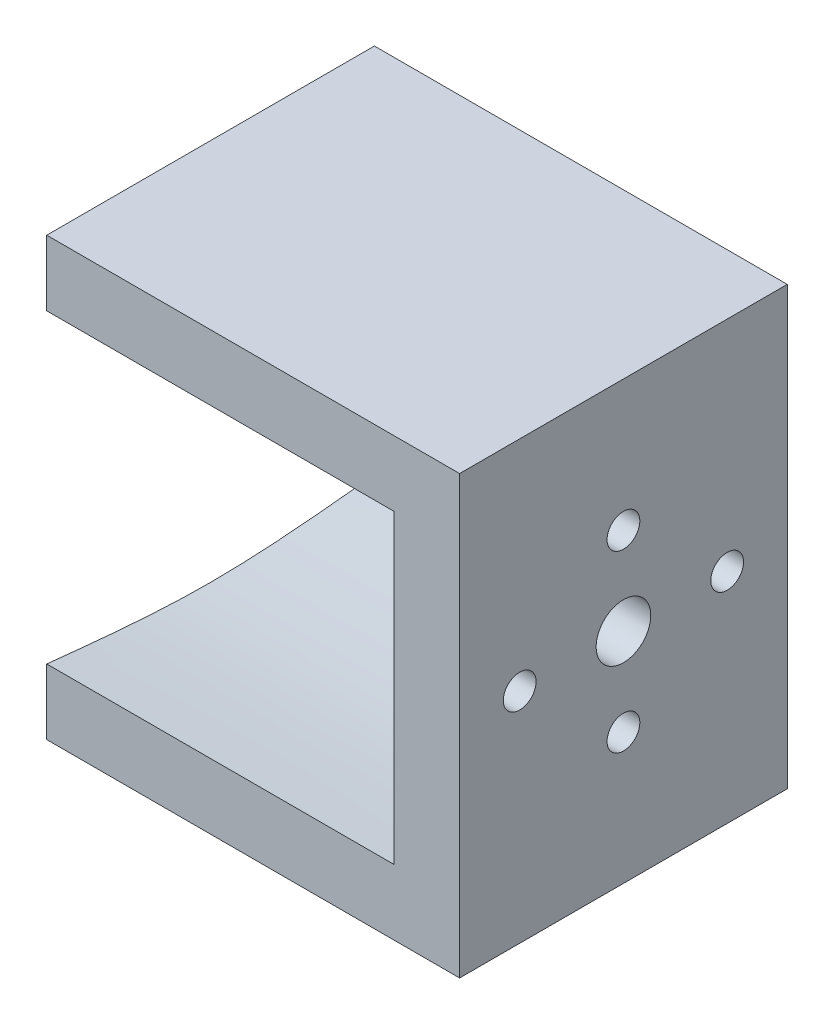
SolidWorks part; units mm, degrees
ref_plane "Front Plane" through (0, 0, 0) normal (0, 0, 1) x (1, 0, 0)
ref_plane "Top Plane" through (0, 0, 0) normal (0, 1, 0) x (1, 0, 0)
ref_plane "Right Plane" through (0, 0, 0) normal (1, 0, 0) x (0, 0, -1)
sketch "Sketch2" plane through (0, 0, 0) normal (0, 0, 1) x (1, 0, 0)
  line L0 (-18.9011, 20) -> (-18.9011, 14)
  line L1 (-18.9011, -20) -> (18.9011, -20)
  line L3 (-18.9011, 20) -> (18.9011, 20)
  line L4 (18.9011, -20) -> (18.9011, 20)
  line L5 (-18.9011, -20) -> (18.9011, 20) construction
  line L6 (-18.9011, 20) -> (18.9011, -20) construction
  line L7 (-18.9011, -14) -> (12.9011, -14)
  line L8 (-18.9011, -14) -> (-18.9011, 14) construction
  line L9 (-18.9011, 14) -> (12.9011, 14)
  line L10 (12.9011, -14) -> (12.9011, 14)
  line L11 (-18.9011, -14) -> (-18.9011, -20)
  line L12 (12.9011, 0) -> (18.9011, 0) construction
  line L13 (12.9011, 14) -> (18.9011, 14) construction
  point P0 (0, 0)
  dimension "D1" = 40
  dimension "D2" = 6
  dimension "D3" = 37.8021
extrude "Boss-Extrude1" add sketch "Sketch2" along normal blind 30 contours L13 L10 L7 L11 L1 L4
sketch "Sketch4" plane through (12.9011, 0, 0) normal (-1, 0, 0) x (0, 0, 1)
  line L0 (30, 0) -> (0, 0) construction
  line L1 (30, -14) -> (30, 14) construction
  line L6 (15, 8) -> (15, -8) construction
  line L7 (24.5, 0) -> (5.5, 0) construction
  circle A0 centre (15, 8) radius 1.5
  circle A1 centre (15, 0) radius 2.5
  circle A2 centre (15, -8) radius 1.5
  circle A3 centre (5.5, 0) radius 1.5
  circle A4 centre (24.5, 0) radius 1.5
  point P10 (0, 0)
  point P11 (32.0379, 0)
  point P14 (0, 0)
  point P15 (15, 0)
  point P16 (12.514, 0)
  point P17 (15, 0)
  point P19 (30, 0)
  point P30 (15, 0)
  dimension "D2" = 3
  dimension "D4" = 5
  dimension "D1" = 8
  dimension "D3" = 9.5
extrude "Cut-Extrude1" cut sketch "Sketch4" against normal through all
sketch "Sketch7" plane through (-18.9011, 0, 0) normal (-1, 0, 0) x (0, 0, 1)
  line L0 (0, -14) -> (30, -14)
  line L1 (16.5, 0) -> (-16.5, 0) construction
  line L2 (0, 14) -> (30, 14)
  spline S0 degree 3 poles (0, -14) (5, -14.5166) (15, -15.5498) (25, -14.5166) (30, -14) knots 0 0 0 0 0.5 1 1 1 1
  spline S1 degree 3 poles (0, 14) (5, 14.5166) (15, 15.5498) (25, 14.5166) (30, 14) knots 0 0 0 0 0.5 1 1 1 1
extrude "Cut-Extrude3" cut sketch "Sketch7" along direction (1, 0, 0) on the side against the normal up to surface (31.8021 mm away)
equation "\"inner radius\"= 230"
equation "\"wall thickness\"= 6\t"
equation "\"outer radius\"= \"inner radius\" + 2 * \"wall thickness\""
equation "\"height\" = 40"
equation "\"wheel distance\" = 100"
equation "\"screw length\" = 15"
equation "\"top bottom thickness\" = 4"
equation "\"accel distance\" = 75"
equation "\"tolerance\" = 0.3"
equation "\"D1@Sketch2\"=\"height\""
equation "\"D2@Sketch2\"=\"wall thickness\""
equation "\"D1@Boss-Extrude1\"=\"wheel hole width\""
equation "\"wheel hole width\" = 30"
